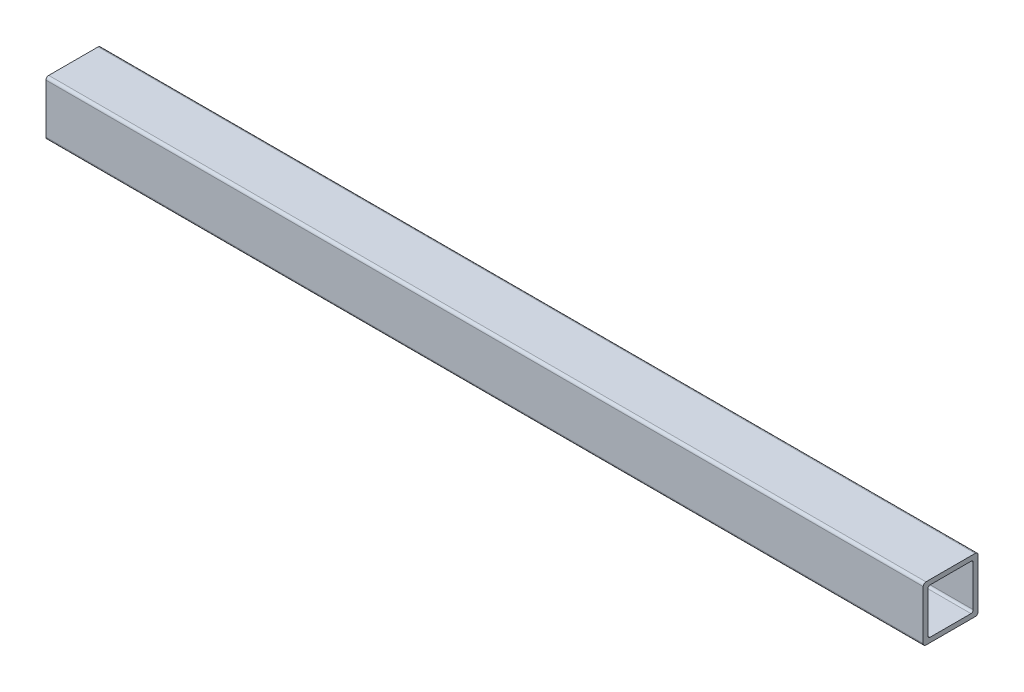
SolidWorks part; units mm, degrees
ref_plane "Front" through (0, 0, 0) normal (0, 0, 1) x (1, 0, 0)
ref_plane "Top" through (0, 0, 0) normal (0, 1, 0) x (1, 0, 0)
ref_plane "Right" through (0, 0, 0) normal (1, 0, 0) x (0, 0, -1)
sketch "Sketch1" plane through (0, 0, 0) normal (1, 0, 0) x (0, 0, -1)
  line L0 (-7.874, 0) -> (-9.525, 0) construction
  line L1 (8.5725, -9.525) -> (-8.5725, -9.525) construction
  line L2 (9.525, -8.5725) -> (9.525, 8.5725) construction
  line L3 (8.5725, 9.525) -> (-8.5725, 9.525) construction
  line L4 (-9.525, -8.5725) -> (-9.525, 8.5725) construction
  line L5 (9.525, -9.525) -> (-9.525, 9.525) construction
  line L6 (9.525, 9.525) -> (-9.525, -9.525) construction
  line L7 (7.0866, 7.874) -> (-7.0866, 7.874) construction
  line L8 (7.874, 7.0866) -> (7.874, -7.0866) construction
  line L9 (7.0866, -7.874) -> (-7.0866, -7.874) construction
  line L10 (-7.874, 7.0866) -> (-7.874, -7.0866) construction
  line L11 (7.874, 7.874) -> (-7.874, -7.874) construction
  line L12 (7.874, -7.874) -> (-7.874, 7.874) construction
  line L13 (0, -7.874) -> (0, -9.525) construction
  line L14 (7.874, -7.0866) -> (7.874, -9.525) construction
  line L15 (7.874, 0) -> (9.525, 0) construction
  line L16 (7.874, -9.525) -> (9.525, -9.525) construction
  arc A0 (-7.0866, -7.874) -> (-7.874, -7.0866) centre (-7.0866, -7.0866) cw construction
  arc A1 (7.874, -7.0866) -> (7.0866, -7.874) centre (7.0866, -7.0866) cw construction
  arc A2 (7.0866, 7.874) -> (7.874, 7.0866) centre (7.0866, 7.0866) cw construction
  arc A3 (-7.0866, 7.874) -> (-7.874, 7.0866) centre (-7.0866, 7.0866) ccw construction
  arc A4 (8.5725, -9.525) -> (9.525, -8.5725) centre (8.5725, -8.5725) ccw construction
  arc A5 (9.525, 8.5725) -> (8.5725, 9.525) centre (8.5725, 8.5725) ccw construction
  arc A6 (-8.5725, 9.525) -> (-9.525, 8.5725) centre (-8.5725, 8.5725) ccw construction
  arc A7 (-8.5725, -9.525) -> (-9.525, -8.5725) centre (-8.5725, -8.5725) cw construction
  point P0 (0, 0)
  point P6 (0, 0)
  dimension "D2" = 0.7874
  dimension "D3" = 0.9525
  dimension "Outside Width" = 19.05
  dimension "Ouside Height" = 19.05
  dimension "Inside Height" = 15.748
  dimension "Wall Thickness" = 1.651
sketch "Sketch2" plane through (0, 0, 0) normal (0, 0, 1) x (1, 0, 0)
  line L0 (-152.4, 0) -> (152.4, 0) construction
  point P3 (-135.001, 0)
  point P4 (135.001, 0)
  dimension "Length" = 304.8
  dimension "D1" = 17.399
  dimension "D2" = 17.399
sketch "Sketch4" plane through (0, 0, 0) normal (1, 0, 0) x (0, 0, -1)
  line L8 (9.525, -8.5725) -> (9.525, 8.5725)
  line L9 (8.5725, 9.525) -> (-8.5725, 9.525)
  line L10 (-9.525, -8.5725) -> (-9.525, 8.5725)
  line L11 (8.5725, -9.525) -> (-8.5725, -9.525)
  line L12 (7.874, 7.0866) -> (7.874, -7.0866)
  line L13 (7.0866, -7.874) -> (-7.0866, -7.874)
  line L14 (-7.874, 7.0866) -> (-7.874, -7.0866)
  line L15 (7.0866, 7.874) -> (-7.0866, 7.874)
  arc A8 (9.525, 8.5725) -> (8.5725, 9.525) centre (8.5725, 8.5725) ccw
  arc A9 (-8.5725, 9.525) -> (-9.525, 8.5725) centre (-8.5725, 8.5725) ccw
  arc A10 (-9.525, -8.5725) -> (-8.5725, -9.525) centre (-8.5725, -8.5725) ccw
  arc A11 (8.5725, -9.525) -> (9.525, -8.5725) centre (8.5725, -8.5725) ccw
  arc A12 (7.0866, -7.874) -> (7.874, -7.0866) centre (7.0866, -7.0866) ccw
  arc A13 (-7.874, -7.0866) -> (-7.0866, -7.874) centre (-7.0866, -7.0866) ccw
  arc A14 (-7.0866, 7.874) -> (-7.874, 7.0866) centre (-7.0866, 7.0866) ccw
  arc A15 (7.874, 7.0866) -> (7.0866, 7.874) centre (7.0866, 7.0866) ccw
extrude "Boss-Extrude1" add sketch "Sketch4" along normal up to vertex (152.4 mm away) and the other way up to vertex (152.4 mm away)
equation "\"D3@Sketch1\"=\"Outside Width@Sketch1\"*.05"
equation "\"D2@Sketch1\" = \"Inside Height@Sketch1\" * .05"
equation "\"D1@Sketch2\"=\"Outside Width@Sketch1\"-\"Wall Thickness@Sketch1\""
equation "\"D2@Sketch2\"=\"D1@Sketch2\""
